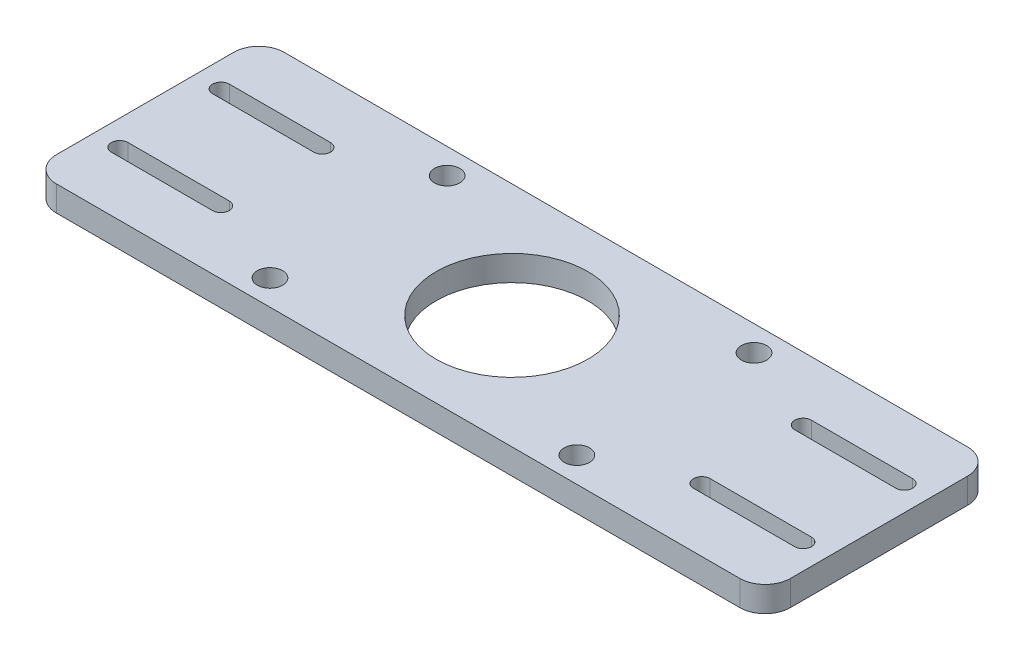
SolidWorks part; units mm, degrees
ref_plane "Ebene vorne" through (0, 0, 0) normal (0, 0, 1) x (1, 0, 0)
ref_plane "Ebene oben" through (0, 0, 0) normal (0, 1, 0) x (1, 0, 0)
ref_plane "Ebene rechts" through (0, 0, 0) normal (1, 0, 0) x (0, 0, -1)
sketch "Sketch1" plane through (0, 0, 0) normal (0, 1, 0) x (1, 0, 0)
  line L0 (0, 0) -> (0, -22.5) construction
  line L1 (72.5, -22.5) -> (-72.5, -22.5)
  line L2 (72.5, -22.5) -> (72.5, 22.5)
  line L3 (72.5, 22.5) -> (-72.5, 22.5)
  line L4 (-72.5, -22.5) -> (-72.5, 22.5)
  line L5 (72.5, -22.5) -> (-72.5, 22.5) construction
  line L6 (72.5, 22.5) -> (-72.5, -22.5) construction
  dimension "D1" = 145
  dimension "D2" = 45
extrude "Boss-Extrude1" add sketch "Sketch1" along normal blind 5
sketch "Sketch2" plane through (0, 5, 0) normal (0, 1, 0) x (1, 0, 0)
  line L0 (-72.5, 0) -> (72.5, 0) construction
  line L1 (-72.5, 22.5) -> (-72.5, -22.5) construction
  line L2 (72.5, -22.5) -> (72.5, 22.5) construction
  line L3 (0, 0) -> (0, -22.5) construction
  line L4 (-72.5, -22.5) -> (72.5, -22.5) construction
  line L5 (-67.5, 8.35) -> (-47.5, 8.35)
  line L6 (-47.5, -11.65) -> (-67.5, -11.65)
  line L7 (-67.5, -8.35) -> (-47.5, -8.35)
  line L8 (-47.5, 11.65) -> (-67.5, 11.65)
  line L9 (47.5, 11.65) -> (67.5, 11.65)
  line L10 (67.5, 8.35) -> (47.5, 8.35)
  line L11 (47.5, -11.65) -> (67.5, -11.65)
  line L12 (67.5, -8.35) -> (47.5, -8.35)
  arc A0 (-67.5, 11.65) -> (-67.5, 8.35) centre (-67.5, 10) ccw
  arc A1 (-47.5, 8.35) -> (-47.5, 11.65) centre (-47.5, 10) ccw
  arc A2 (-47.5, -8.35) -> (-47.5, -11.65) centre (-47.5, -10) cw
  arc A3 (-67.5, -11.65) -> (-67.5, -8.35) centre (-67.5, -10) cw
  arc A4 (67.5, 11.65) -> (67.5, 8.35) centre (67.5, 10) cw
  arc A5 (47.5, 8.35) -> (47.5, 11.65) centre (47.5, 10) cw
  arc A6 (47.5, -8.35) -> (47.5, -11.65) centre (47.5, -10) ccw
  arc A7 (67.5, -11.65) -> (67.5, -8.35) centre (67.5, -10) ccw
  dimension "D1" = 3.3
  dimension "D2" = 5
  dimension "D3" = 20
  dimension "D4" = 10
extrude "Cut-Extrude1" cut sketch "Sketch2" against normal through all
fillet "Fillet1" radius 5 1 edges at (72.5, 2.5, -22.5)
fillet "Fillet2" radius 5 1 edges at (-72.5, 2.5, -22.5)
fillet "Fillet3" radius 5 1 edges at (-72.5, 2.5, 22.5)
fillet "Fillet4" radius 5 1 edges at (72.5, 2.5, 22.5)
sketch "Sketch3" plane through (0, 5, 0) normal (0, 1, 0) x (1, 0, 0)
  circle A1 centre (30.3109, 17.5) radius 2.5
  circle A2 centre (30.3109, -17.5) radius 2.5
  circle A4 centre (-30.3109, -17.5) radius 2.5
  circle A5 centre (-30.3109, 17.5) radius 2.5
  point P15 (0, 0)
  point P18 (0, 0)
extrude "Cut-Extrude2" cut sketch "Sketch3" against normal through all
sketch "Sketch4" plane through (0, 5, 0) normal (0, 1, 0) x (1, 0, 0)
  circle A0 centre (0, 0) radius 15
  dimension "D1" = 30
extrude "Cut-Extrude3" cut sketch "Sketch4" against normal through all
